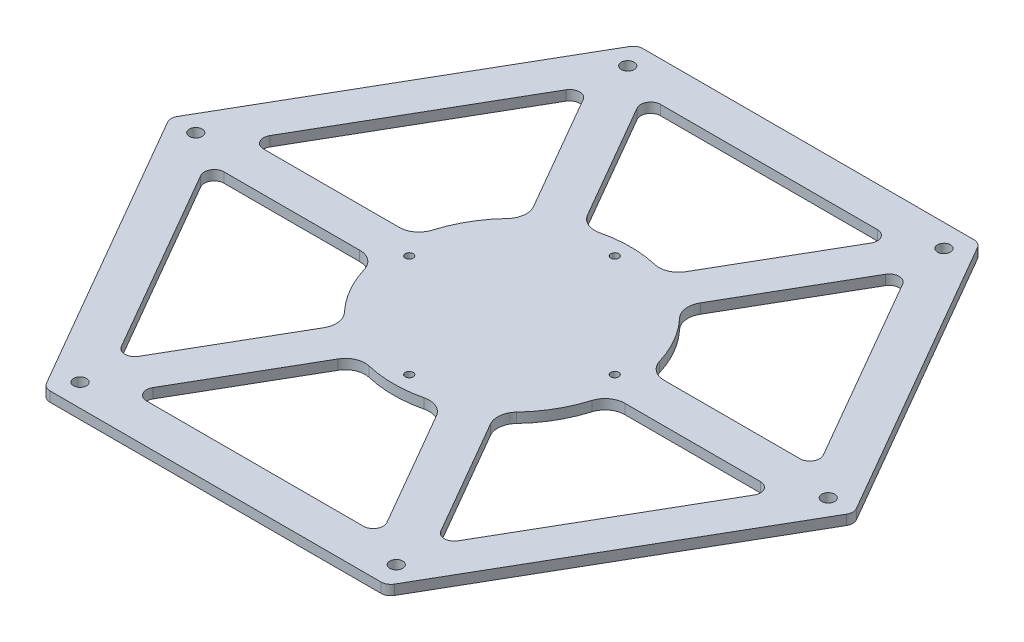
SolidWorks part; units mm, degrees
material "6061-T6 (SS)"
ref_plane "Front Plane" through (0, 0, 0) normal (0, 0, 1) x (1, 0, 0)
ref_plane "Top Plane" through (0, 0, 0) normal (0, 1, 0) x (1, 0, 0)
ref_plane "Right Plane" through (0, 0, 0) normal (1, 0, 0) x (0, 0, -1)
sketch "Sketch1" plane through (0, 0, 0) normal (0, 1, 0) x (1, 0, 0)
  line L0 (-75.0555, 130) -> (-150.1111, 0) construction
  line L7 (171.7617, 2.5) -> (88.0459, 147.5)
  line L8 (83.7158, 150) -> (-83.7158, 150)
  line L9 (-88.0459, 147.5) -> (-171.7617, 2.5)
  line L10 (-171.7617, -2.5) -> (-88.0459, -147.5)
  line L11 (-83.7158, -150) -> (83.7158, -150)
  line L12 (88.0459, -147.5) -> (171.7617, -2.5)
  line L13 (-76.4989, 112.5) -> (-8.6603, -5)
  line L14 (-59.1784, 122.5) -> (8.6603, 5)
  line L15 (-85.1592, 112.5) -> (-140.0074, 17.5)
  line L16 (-140.0074, -17.5) -> (-85.1592, -112.5)
  line L17 (-54.8483, -130) -> (54.8483, -130)
  line L18 (85.1592, -112.5) -> (140.0074, -17.5)
  line L19 (140.0074, 17.5) -> (85.1592, 112.5)
  line L20 (54.8483, 130) -> (-54.8483, 130)
  line L21 (75.0555, 130) -> (-75.0555, 130) construction
  line L22 (150.1111, 0) -> (75.0555, 130) construction
  line L23 (-150.1111, 0) -> (-75.0555, -130) construction
  line L24 (-75.0555, -130) -> (75.0555, -130) construction
  line L25 (75.0555, -130) -> (150.1111, 0) construction
  line L26 (59.1784, 122.5) -> (-8.6603, 5)
  line L27 (76.4989, 112.5) -> (8.6603, -5)
  line L28 (54.8483, 130) -> (-54.8483, 130)
  line L29 (140.0074, 17.5) -> (85.1592, 112.5)
  line L30 (135.6773, 10) -> (0, 10)
  line L31 (135.6773, -10) -> (0, -10)
  line L32 (140.0074, 17.5) -> (85.1592, 112.5)
  line L33 (85.1592, -112.5) -> (140.0074, -17.5)
  line L34 (76.4989, -112.5) -> (8.6603, 5)
  line L35 (59.1784, -122.5) -> (-8.6603, -5)
  line L36 (85.1592, -112.5) -> (140.0074, -17.5)
  line L37 (-54.8483, -130) -> (54.8483, -130)
  line L38 (-59.1784, -122.5) -> (8.6603, -5)
  line L39 (-76.4989, -112.5) -> (-8.6603, 5)
  line L40 (-54.8483, -130) -> (54.8483, -130)
  line L41 (-140.0074, -17.5) -> (-85.1592, -112.5)
  line L42 (-135.6773, -10) -> (0, -10)
  line L43 (-135.6773, 10) -> (0, 10)
  line L44 (-140.0074, -17.5) -> (-85.1592, -112.5)
  line L45 (-85.1592, 112.5) -> (-140.0074, 17.5)
  line L46 (0, 0) -> (52, 0)
  circle A1 centre (0, 0) radius 173.2051 construction
  circle A2 centre (-80, 138.5641) radius 3.25
  circle A3 centre (80, 138.5641) radius 3.25
  circle A4 centre (160, 0) radius 3.25
  circle A5 centre (80, -138.5641) radius 3.25
  circle A6 centre (-80, -138.5641) radius 3.25
  circle A7 centre (-160, 0) radius 3.25
  arc A8 (83.7158, -150) -> (88.0459, -147.5) centre (83.7158, -145) ccw
  arc A9 (-88.0459, -147.5) -> (-83.7158, -150) centre (-83.7158, -145) ccw
  arc A10 (-171.7617, 2.5) -> (-171.7617, -2.5) centre (-167.4316, 0) ccw
  arc A11 (171.7617, 2.5) -> (171.7617, -2.5) centre (167.4316, 0) cw
  arc A12 (88.0459, 147.5) -> (83.7158, 150) centre (83.7158, 145) ccw
  arc A13 (-83.7158, 150) -> (-88.0459, 147.5) centre (-83.7158, 145) ccw
  arc A20 (-75.0555, 130) -> (-75.0555, 130) centre (-75.0555, 130) ccw
  arc A21 (-76.4989, 112.5) -> (-85.1592, 112.5) centre (-80.829, 110) ccw
  arc A22 (-54.8483, 130) -> (-59.1784, 122.5) centre (-54.8483, 125) ccw
  circle A23 centre (0, 0) radius 45
  arc A24 (75.0555, 130) -> (75.0555, 130) centre (75.0555, 130) ccw construction
  circle A25 centre (0, 0) radius 60
  arc A26 (-150.1111, 0) -> (-150.1111, 0) centre (-150.1111, 0) ccw construction
  arc A28 (-75.0555, -130) -> (-75.0555, -130) centre (-75.0555, -130) ccw construction
  arc A30 (75.0555, -130) -> (75.0555, -130) centre (75.0555, -130) ccw construction
  arc A32 (150.1111, 0) -> (150.1111, 0) centre (150.1111, 0) cw construction
  arc A33 (59.1784, 122.5) -> (54.8483, 130) centre (54.8483, 125) ccw
  arc A34 (85.1592, 112.5) -> (76.4989, 112.5) centre (80.829, 110) ccw
  arc A35 (135.6773, 10) -> (140.0074, 17.5) centre (135.6773, 15) ccw
  arc A36 (140.0074, -17.5) -> (135.6773, -10) centre (135.6773, -15) ccw
  arc A37 (76.4989, -112.5) -> (85.1592, -112.5) centre (80.829, -110) ccw
  arc A38 (54.8483, -130) -> (59.1784, -122.5) centre (54.8483, -125) ccw
  arc A39 (-59.1784, -122.5) -> (-54.8483, -130) centre (-54.8483, -125) ccw
  arc A40 (-85.1592, -112.5) -> (-76.4989, -112.5) centre (-80.829, -110) ccw
  arc A41 (-135.6773, -10) -> (-140.0074, -17.5) centre (-135.6773, -15) ccw
  arc A42 (-140.0074, 17.5) -> (-135.6773, 10) centre (-135.6773, 15) ccw
  circle A44 centre (52, 0) radius 2
  circle A45 centre (0, -52) radius 2
  circle A46 centre (-52, 0) radius 2
  circle A47 centre (0, 52) radius 2
  point P5 (86.6025, -150)
  point P25 (0, 0)
  point P27 (-86.6025, -150)
  point P30 (-173.2051, 0)
  point P33 (173.2051, 0)
  point P36 (86.6025, 150)
  point P39 (-86.6025, 150)
  point P79 (0, 0)
  point P80 (0, 0)
  point P134 (0, 0)
  dimension "D2" = 6
  dimension "D3" = 5
  dimension "D4" = 5
  dimension "D5" = 5
  dimension "D7" = 6.5
  dimension "D8" = 4
  dimension "D1" = 300
  dimension "D6" = 20
  dimension "D9" = 6
extrude "Boss-Extrude1" add sketch "Sketch1" along normal blind 5
fillet "Fillet2" radius 10 12 edges at (-59.1608, 2.5, -10) (-38.2407, 2.5, -46.2348) (-20.9201, 2.5, -56.2348) (20.9201, 2.5, -56.2348) (38.2407, 2.5, -46.2348) (59.1608, 2.5, -10) (59.1608, 2.5, 10) (38.2407, 2.5, 46.2348) (-38.2407, 2.5, 46.2348) (-20.9201, 2.5, 56.2348) (20.9201, 2.5, 56.2348) (-59.1608, 2.5, 10)
